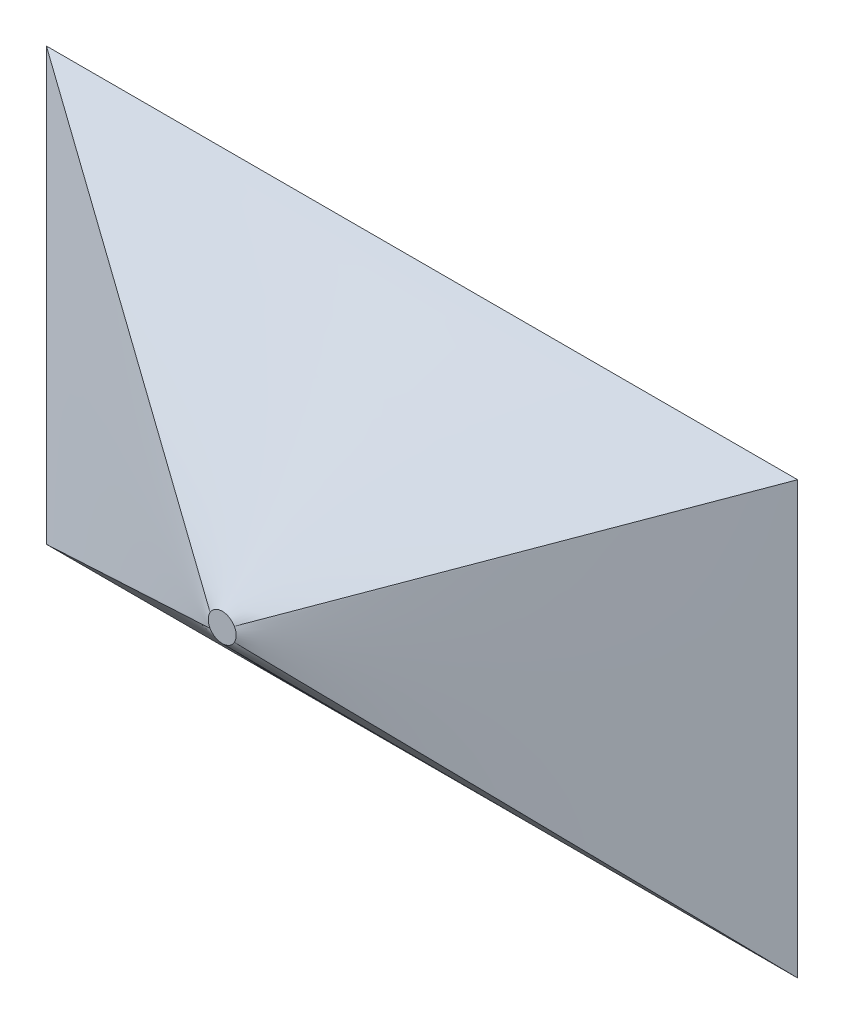
SolidWorks part; units mm, degrees
ref_plane "Alzado" through (0, 0, 0) normal (0, 0, 1) x (1, 0, 0)
ref_plane "Planta" through (0, 0, 0) normal (0, 1, 0) x (1, 0, 0)
ref_plane "Vista lateral" through (0, 0, 0) normal (1, 0, 0) x (0, 0, -1)
sketch "Croquis1" plane through (0, 0, 0) normal (0, 0, 1) x (1, 0, 0)
  line L5 (-188, 108) -> (188, 108)
  line L6 (-188, 108) -> (-188, -108)
  line L7 (-188, -108) -> (188, -108)
  line L8 (188, 108) -> (188, -108)
  line L9 (-188, 108) -> (188, -108) construction
  line L10 (-188, -108) -> (188, 108) construction
  point P0 (0, 0)
  dimension "D1" = 376
  dimension "D2" = 216
ref_plane "Plano2" through (0, 0, 0) normal (0, 0, 1) x (1, 0, 0)
ref_plane "Plano3" through (0, 0, 100) normal (0, 0, 1) x (1, 0, 0)
sketch "Croquis2" plane through (0, 0, 100) normal (0, 0, 1) x (1, 0, 0)
  circle A0 centre (0, 0) radius 7
loft "Recubrir2" add profiles "Croquis2", "Croquis1"
